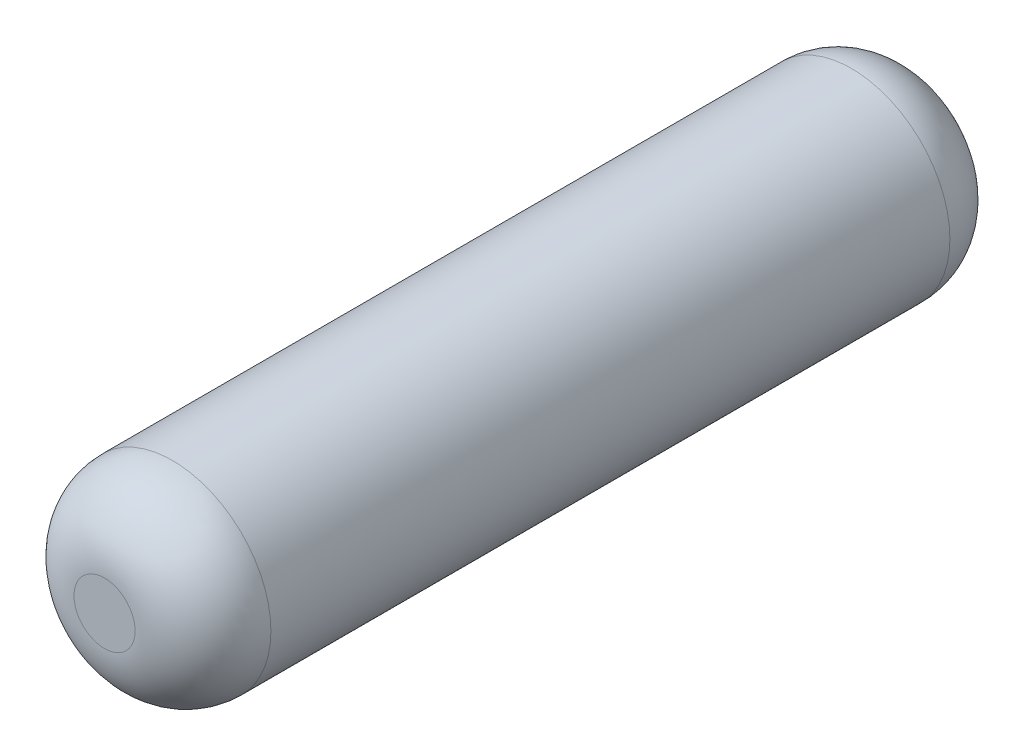
SolidWorks part; units mm, degrees
ref_plane "Front Plane" through (0, 0, 0) normal (1, 0, 0) x (0, 1, 0)
ref_plane "Top Plane" through (0, 0, 0) normal (0, 0, 1) x (0, 1, 0)
ref_plane "Right Plane" through (0, 0, 0) normal (0, 1, 0) x (-1, 0, 0)
sketch "Sketch1" plane through (0, 0, 0) normal (0, 0, 1) x (0, 1, 0)
  circle A0 centre (0, 0) radius 1.45
  dimension "D1" = 2.9
extrude "Boss-Extrude1" add sketch "Sketch1" against normal blind 12
fillet "Fillet1" radius 1 2 edges at (1.45, 0, -12) (1.45, 0, 0)
scale "Scale1" scale about centroid uniform scaling yes scale factor 0.7
